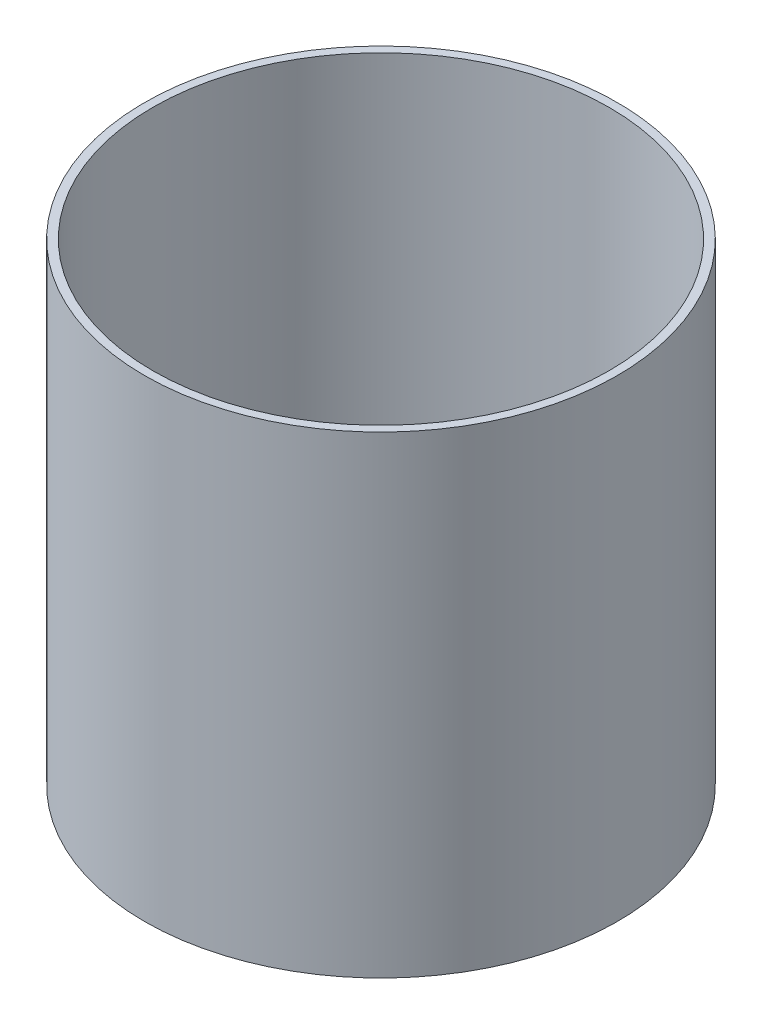
SolidWorks part; units mm, degrees
ref_plane "Front Plane" through (0, 0, 0) normal (0, 0, 1) x (1, 0, 0)
ref_plane "Top Plane" through (0, 0, 0) normal (0, 1, 0) x (1, 0, 0)
ref_plane "Right Plane" through (0, 0, 0) normal (1, 0, 0) x (0, 0, -1)
sketch "Sketch1" plane through (0, 0, 0) normal (0, 1, 0) x (1, 0, 0)
  circle A0 centre (0, 0) radius 50
  circle A1 centre (0, 0) radius 48.25
  dimension "D1" = 100
  dimension "D2" = 96.5
extrude "Boss-Extrude1" add sketch "Sketch1" along normal blind 100
sketch "Sketch2" plane through (0, 0, 0) normal (0, -1, 0) x (1, 0, 0)
  circle A0 centre (0, 0) radius 50
extrude "Boss-Extrude2" add sketch "Sketch2" against normal blind 1.5
sketch "Sketch3" plane through (0, 0, 0) normal (0, -1, 0) x (1, 0, 0)
  line L1 (-20, 15) -> (20, 15)
  line L2 (-20, 15) -> (-20, -15)
  line L3 (-20, -15) -> (20, -15)
  line L4 (20, 15) -> (20, -15)
  line L5 (-20, 15) -> (20, -15) construction
  line L6 (-20, -15) -> (20, 15) construction
  circle A0 centre (-20, 0) radius 7.25
  circle A1 centre (20, 0) radius 7.25
  point P0 (0, 0)
  dimension "D3" = 14.5
  dimension "D4" = 14.5
  dimension "D1" = 40
  dimension "D2" = 30
extrude "Cut-Extrude1" cut sketch "Sketch3" against normal blind 2.5 contours A1 | A0
